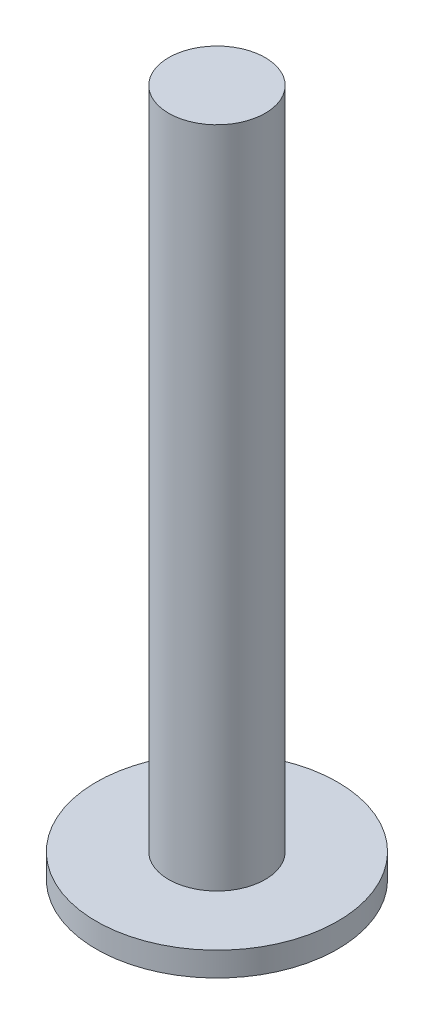
SolidWorks part; units mm, degrees
ref_plane "Front Plane" through (0, 0, 0) normal (0, 0, 1) x (1, 0, 0)
ref_plane "Top Plane" through (0, 0, 0) normal (0, 1, 0) x (1, 0, 0)
ref_plane "Right Plane" through (0, 0, 0) normal (1, 0, 0) x (0, 0, -1)
sketch "Sketch5" plane through (0, 0, 0) normal (0, 1, 0) x (1, 0, 0)
  circle A0 centre (0, 0) radius 40
  dimension "D1" = 80
extrude "Boss-Extrude3" add sketch "Sketch5" along normal blind 550 contours A0
sketch "Sketch6" plane through (0, 0, 0) normal (0, -1, 0) x (1, 0, 0)
  circle A0 centre (0, 0) radius 100
  dimension "D1" = 200
extrude "Boss-Extrude4" add sketch "Sketch6" along normal blind 20
